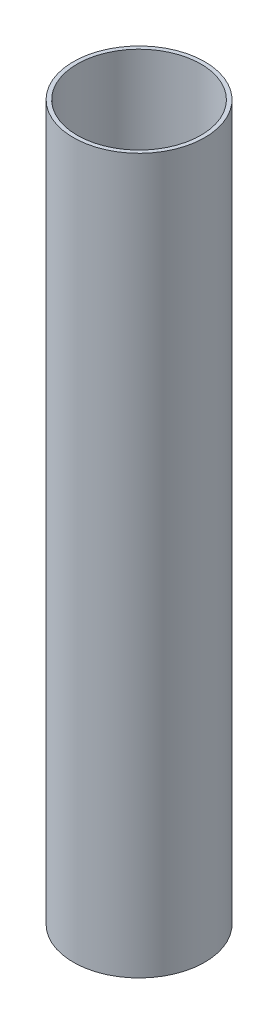
SolidWorks part; units mm, degrees
material "Glass"
ref_plane "Front Plane" through (0, 0, 0) normal (0, 0, 1) x (1, 0, 0)
ref_plane "Top Plane" through (0, 0, 0) normal (0, 1, 0) x (1, 0, 0)
ref_plane "Right Plane" through (0, 0, 0) normal (1, 0, 0) x (0, 0, -1)
sketch "Sketch1" plane through (0, 0, 0) normal (0, 0, 1) x (1, 0, 0)
  line L0 (-5.3266, 38.5) -> (-14.2, 35.5) construction
  line L1 (-13.35, 35.7874) -> (13.35, 35.7874)
  line L2 (-13.35, 35.7874) -> (-13.35, 180.7874)
  line L3 (-13.35, 180.7874) -> (13.35, 180.7874)
  line L4 (13.35, 35.7874) -> (13.35, 180.7874)
  line L5 (0, 0) -> (0, 197.72) construction
  dimension "D1" = 26.7
  dimension "D2" = 145
revolve "Revolve1" add sketch "Sketch1" angle 360 about L5
sketch "Sketch2" plane through (0, 180.7874, 0) normal (0, 1, 0) x (1, 0, 0)
  circle A0 centre (0, 0) radius 12.55
  circle A1 centre (0, 0) radius 13.35 construction
  dimension "D1" = 0.8
extrude "Cut-Extrude1" cut sketch "Sketch2" against normal blind 158
